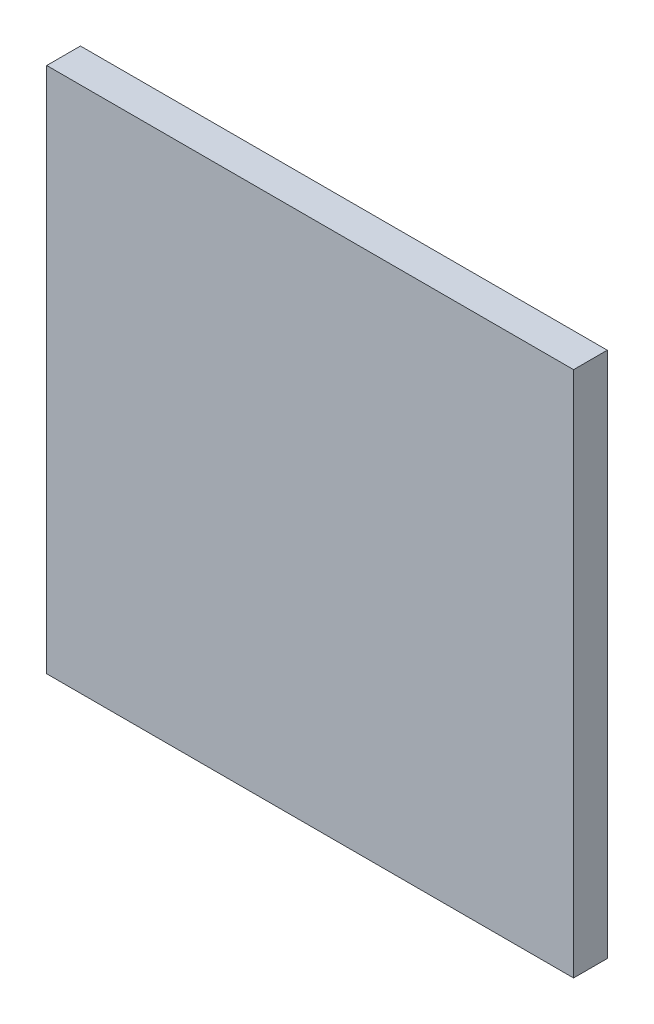
SolidWorks part; units mm, degrees
ref_plane "Front Plane" through (0, 0, 0) normal (0, 0, 1) x (1, 0, 0)
ref_plane "Top Plane" through (0, 0, 0) normal (0, 1, 0) x (1, 0, 0)
ref_plane "Right Plane" through (0, 0, 0) normal (1, 0, 0) x (0, 0, -1)
sketch "Sketch1" plane through (0, 0, 0) normal (0, 0, 1) x (1, 0, 0)
  line L1 (0, 0) -> (12.5, 0)
  line L2 (0, 0) -> (0, 12.5)
  line L3 (0, 12.5) -> (12.5, 12.5)
  line L4 (12.5, 0) -> (12.5, 12.5)
  dimension "D1" = 12.5
extrude "Boss-Extrude1" add sketch "Sketch1" along normal blind 0.8
